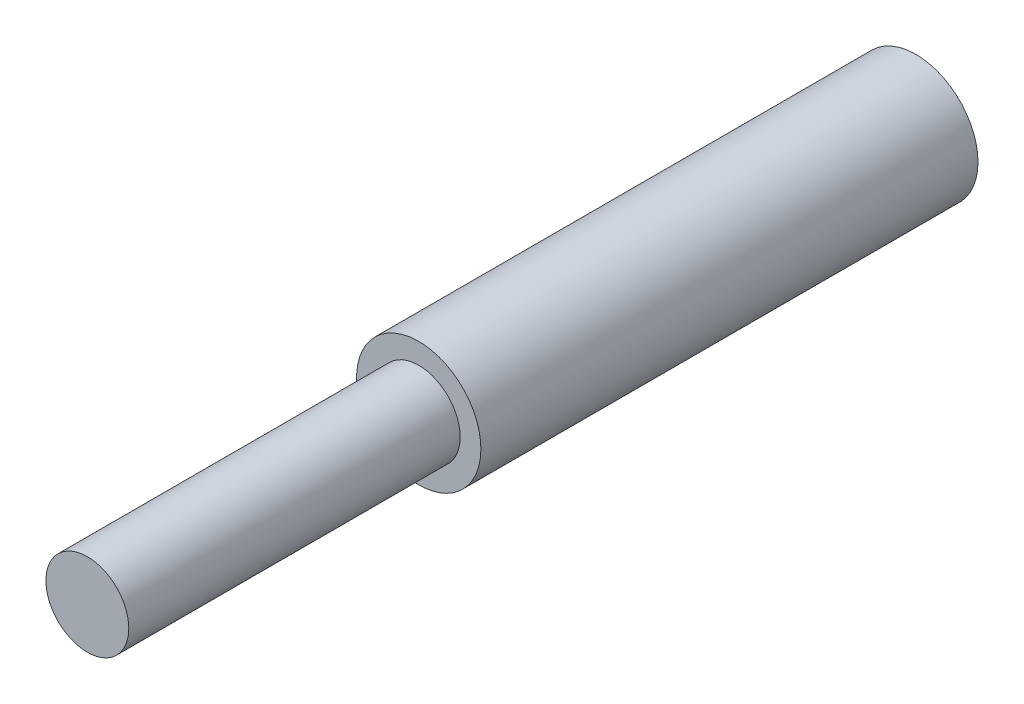
SolidWorks part; units mm, degrees
ref_plane "前视基准面" through (0, 0, 0) normal (0, 0, 1) x (1, 0, 0)
ref_plane "上视基准面" through (0, 0, 0) normal (0, 1, 0) x (1, 0, 0)
ref_plane "右视基准面" through (0, 0, 0) normal (1, 0, 0) x (0, 0, -1)
sketch "草图1" plane through (0, 0, 0) normal (0, 0, 1) x (1, 0, 0)
  circle A0 centre (0, 0) radius 7.5
  dimension "D1" = 15
extrude "凸台-拉伸1" add sketch "草图1" along normal blind 100
sketch "草图2" plane through (0, 0, 100) normal (0, 0, 1) x (1, 0, 0)
  circle A0 centre (0, 0) radius 5
  dimension "D1" = 10
extrude "切除-拉伸1" cut sketch "草图2" against normal blind 40 flip side to cut
sketch "草图23" plane through (-0.0071, -3.4297, 100) normal (0, 0, 1) x (1, 0, 0)
  line L0 (0.0071, 3.4297) -> (5.0071, 3.4297) construction
  line L1 (0.0071, 3.4297) -> (-4.9929, 3.4297) construction
  line L2 (0.0071, 3.4297) -> (0.0071, -1.5703) construction
  circle A0 centre (0.0071, 3.4297) radius 5
  circle A2 centre (0.0071, 3.4297) radius 5 construction
  point P2 (5.0071, 3.4297)
  point P3 (0.0071, 8.4297)
  point P10 (-4.9929, 3.4297)
  point P15 (0.0071, -1.5703)
  dimension "D1" = 10
  dimension "D2" = 180
ref_plane "基准面1" through (-5, 0, 100) normal (0, -1, 0) x (0, 0, 1)
sketch "草图33" plane through (-20, 0, 100) normal (0, -1, 0) x (0, 0, 1)
  line L0 (0, -20) -> (88.3402, -20) construction
  line L1 (-38.5, -20) -> (-26.5, -20) construction
  line L2 (-38.5, -18.5) -> (-26.5, -18.5)
  line L3 (-38.5, -21.5) -> (-26.5, -21.5)
  line L4 (0, -25) -> (0, -15) construction
  arc A0 (-38.5, -18.5) -> (-38.5, -21.5) centre (-38.5, -20) ccw
  arc A1 (-26.5, -21.5) -> (-26.5, -18.5) centre (-26.5, -20) ccw
  point P6 (-32.5, -20)
  point P12 (-25, -20)
  dimension "D3" = 25
  dimension "D1" = 3
  dimension "D2" = 12
extrude "切除-拉伸13" cut sketch "草图33" against normal blind 1.8 from vertex at 5 starting at point (0, -5, 100)
other "轴键槽特征库<1>"
other "M10 机械螺纹 螺柱1" parameters "D1"=10, "D2"=10, "D3"=10, "D4"=10
sketch "草图3" plane through (0, 0, 100) normal (1, 0, 0) x (0, 1, 0)
  line L5 (0, -14.3089) -> (0, 0) construction
  line L6 (4.188, 0) -> (5, -0.812)
  line L9 (5, -0.812) -> (5, -10) construction
  line L10 (4.188, 0) -> (5, 0)
  line L13 (5, -0.812) -> (5, 0)
  point P2 (4, -0.8509)
  point P8 (4.3777, -10)
  dimension "Minor Diameter" = 8.376
  dimension "Major Diameter" = 10
  dimension "Thread Length" = 10
  dimension "Chamfer Angle" = 45
cosmetic thread "螺柱螺纹1"
